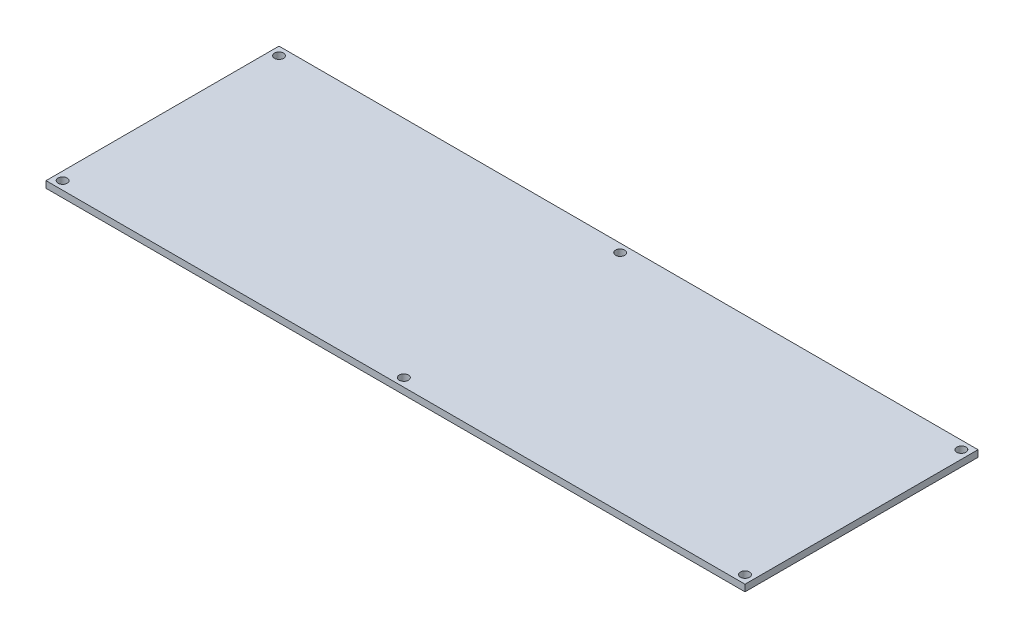
SolidWorks part; units mm, degrees
ref_plane "Front Plane" through (0, 0, 0) normal (0, 0, 1) x (1, 0, 0)
ref_plane "Top Plane" through (0, 0, 0) normal (0, 1, 0) x (1, 0, 0)
ref_plane "Right Plane" through (0, 0, 0) normal (1, 0, 0) x (0, 0, -1)
sketch "Sketch1" plane through (0, 0, 0) normal (0, 1, 0) x (1, 0, 0)
  line L0 (0, 59.1701) -> (0, -53.9284) construction
  line L1 (-105, 35) -> (105, 35)
  line L2 (-105, 35) -> (-105, -35)
  line L3 (-105, -35) -> (105, -35)
  line L4 (105, 35) -> (105, -35)
  line L5 (-105, 35) -> (105, -35) construction
  line L6 (-105, -35) -> (105, 35) construction
  line L7 (-77.6976, 0) -> (103.4947, 0) construction
  line L8 (-51.25, 59.1701) -> (-51.25, -53.9284) construction
  circle A0 centre (-102.5, 32.5) radius 1.375
  circle A1 centre (-102.5, -32.5) radius 1.375
  circle A2 centre (0, -32.5) radius 1.375
  circle A3 centre (0, 32.5) radius 1.375
  circle A4 centre (102.5, -32.5) radius 1.375
  circle A5 centre (102.5, 32.5) radius 1.375
  point P0 (0, 0)
  dimension "D3" = 2.5
  dimension "D4" = 2.75
  dimension "D1" = 210
  dimension "D2" = 70
  dimension "D5" = 102.5
  dimension "D6" = 2.5
  dimension "D7" = 2.5
  dimension "D8" = 65
extrude "Boss-Extrude1" add sketch "Sketch1" along normal mid plane 2
